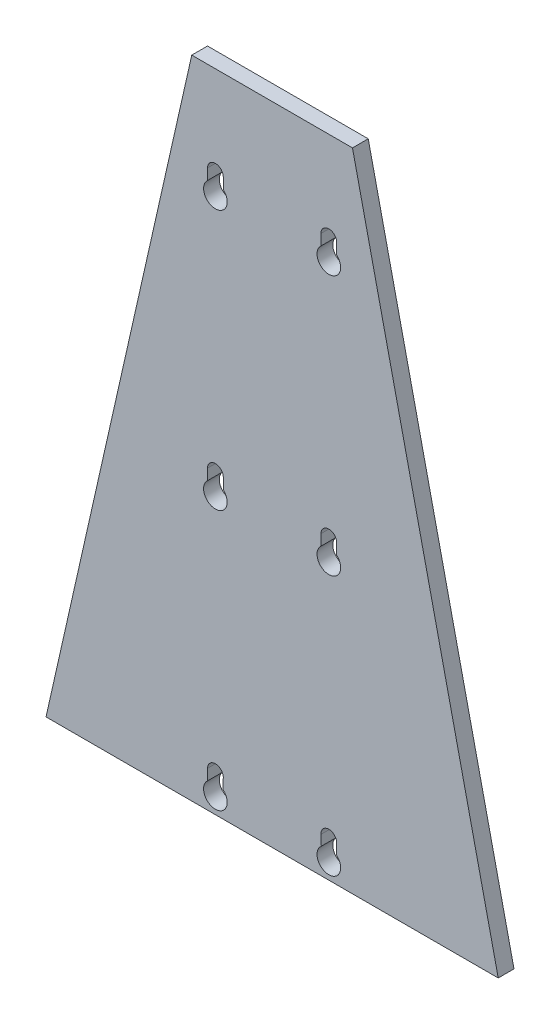
SolidWorks part; units mm, degrees
ref_plane "前视基准面" through (0, 0, 0) normal (0, 0, 1) x (1, 0, 0)
ref_plane "上视基准面" through (0, 0, 0) normal (0, 1, 0) x (1, 0, 0)
ref_plane "右视基准面" through (0, 0, 0) normal (1, 0, 0) x (0, 0, -1)
sketch "草图1" plane through (0, 0, 0) normal (0, 0, 1) x (1, 0, 0)
  line L0 (-41, 0) -> (41, 0)
  line L1 (0, 0) -> (0, -400)
  line L5 (0, -400) -> (0, -410)
  line L6 (-143.5, -410) -> (-51, 0)
  line L7 (-143.5, -410) -> (143.5, -410)
  line L8 (-36, -399.5) -> (-36, -387)
  line L9 (143.5, -410) -> (51, 0)
  line L10 (-41, -387) -> (-41, -393.9098)
  line L12 (-36, -400) -> (-36, -399.5)
  line L13 (-31, -387) -> (-31.1898, -393.7457)
  line L15 (-36, -410) -> (-36, -407)
  line L16 (-36, -407) -> (-36, -399.5)
  line L17 (-36, -387) -> (-36, -222) construction
  line L19 (-36, -222) -> (-36, -234.5)
  line L20 (41, 0) -> (51, 0)
  line L21 (-41, -222) -> (-41, -228.9098)
  line L22 (-31, -222) -> (-31, -228.9098)
  line L23 (41, -387) -> (41, -393.9098)
  line L24 (31, -387) -> (31.1898, -393.7457)
  line L25 (31, -222) -> (31, -228.9098)
  line L26 (41, -222) -> (41, -228.9098)
  line L27 (-36, -222) -> (-36, -57) construction
  line L28 (-41, 0) -> (-51, 0)
  line L29 (-36, -57) -> (-36, -69.5)
  line L30 (-41, -57) -> (-41, -63.9098)
  line L31 (-31, -57) -> (-31, -63.9098)
  line L32 (31, -57) -> (31, -63.9098)
  line L33 (41, -57) -> (41, -63.9098)
  arc A8 (-41, -393.9098) -> (-31.1898, -393.7457) centre (-36, -399.5) ccw
  arc A9 (-31.0079, -387.2811) -> (-41, -387) centre (-36, -387) ccw
  arc A10 (-31, -222) -> (-41, -222) centre (-36, -222) ccw
  arc A11 (-41, -228.9098) -> (-31, -228.9098) centre (-36, -234.5) ccw
  arc A12 (31.0079, -387.2811) -> (41, -387) centre (36, -387) cw
  arc A13 (41, -393.9098) -> (31.1898, -393.7457) centre (36, -399.5) cw
  arc A14 (41, -228.9098) -> (31, -228.9098) centre (36, -234.5) cw
  arc A15 (31, -222) -> (41, -222) centre (36, -222) cw
  arc A16 (-31, -57) -> (-41, -57) centre (-36, -57) ccw
  arc A17 (-41, -63.9098) -> (-31, -63.9098) centre (-36, -69.5) ccw
  arc A18 (41, -63.9098) -> (31, -63.9098) centre (36, -69.5) cw
  arc A19 (31, -57) -> (41, -57) centre (36, -57) cw
  point P4 (0, 0)
  point P10 (0, -400)
  point P15 (0, -400)
  dimension "D1" = 23
extrude "凸台-拉伸1" add sketch "草图1" along normal blind 10
